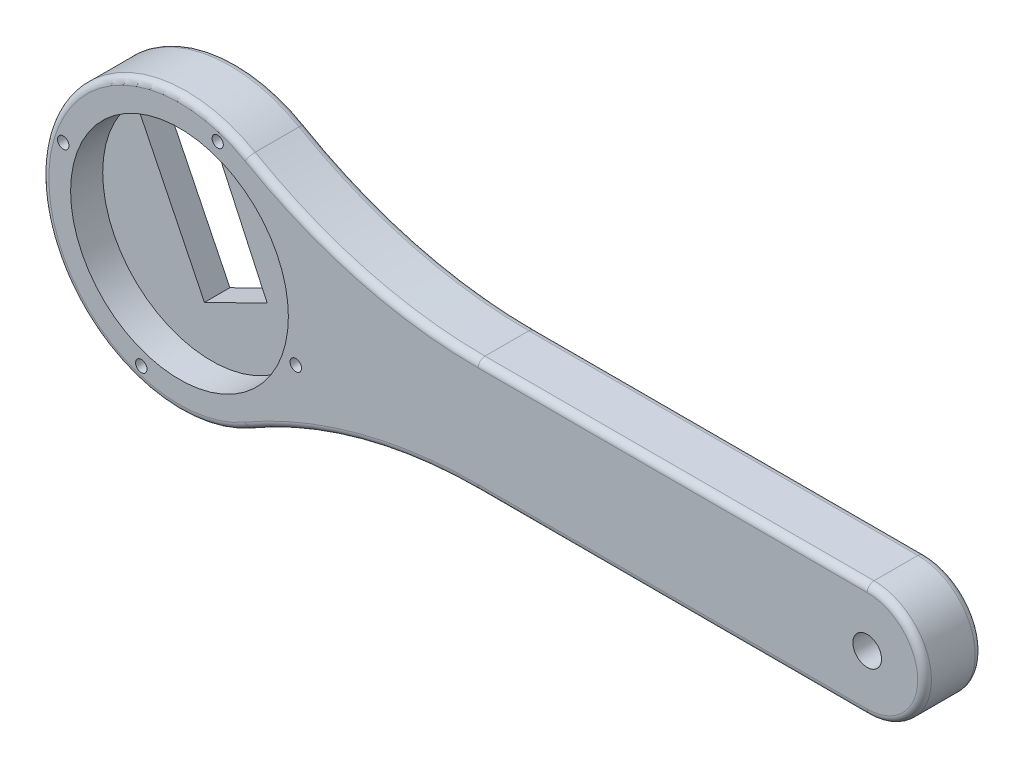
SolidWorks part; units mm, degrees
ref_plane "Front Plane" through (0, 0, 0) normal (0, 0, 1) x (1, 0, 0)
ref_plane "Top Plane" through (0, 0, 0) normal (0, 1, 0) x (1, 0, 0)
ref_plane "Right Plane" through (0, 0, 0) normal (1, 0, 0) x (0, 0, -1)
sketch "Sketch1" plane through (0, 0, 0) normal (0, 0, 1) x (1, 0, 0)
  line L0 (0, 0) -> (300, 0) construction
  line L1 (54.5436, 25) -> (300, 25)
  line L2 (54.5436, -25) -> (300, -25)
  arc A0 (54.5436, 25) -> (54.5436, -25) centre (0, 0) ccw
  arc A2 (300, -25) -> (300, 25) centre (300, 0) ccw
  circle A3 centre (300, 0) radius 6.25
  dimension "D1" = 120
  dimension "D2" = 50
  dimension "D5" = 12.5
  dimension "D3" = 300
  dimension "D4" = 245.4564
extrude "Boss-Extrude1" add sketch "Sketch1" along normal blind 25.1
sketch "Sketch2" plane through (0, 0, 25.1) normal (0, 0, 1) x (1, 0, 0)
  circle A0 centre (-16.6647, -50.7331) radius 2.495
  circle A1 centre (-50.7331, 16.6647) radius 2.5
  circle A2 centre (16.6647, 50.7331) radius 2.4444
  circle A3 centre (50.7331, -16.6647) radius 2.5
sketch "Sketch3" plane through (0, 0, 25.1) normal (0, 0, 1) x (1, 0, 0)
  circle A0 centre (0, 0) radius 47.5
  dimension "D1" = 95
extrude "Cut-Extrude2" cut sketch "Sketch3" against normal blind 14
extrude "Cut-Extrude5" cut sketch "Sketch2" against normal through all both and the other way through all
sketch "Sketch6" plane through (0, 0, 0) normal (0, 0, -1) x (-1, 0, 0)
  circle A0 centre (11.9735, 47.2126) radius 3
  circle A1 centre (27.3813, 40.0293) radius 3
  circle A2 centre (-19.7177, -20.7629) radius 3
  circle A3 centre (-4.3099, -27.9462) radius 3
  dimension "D1" = 6
  dimension "D2" = 6
  dimension "D3" = 6
  dimension "D4" = 6
extrude "Cut-Extrude6" cut sketch "Sketch6" against normal blind 6
sketch "Sketch7" plane through (0, 0, 11.1) normal (0, 0, 1) x (1, 0, 0)
  line L0 (-32.4009, 32.8719) -> (-3.109, -26.9124)
  line L1 (-3.109, -26.9124) -> (24.2542, -13.5055)
  line L2 (24.2542, -13.5055) -> (-3.6508, 46.9583)
  line L3 (-3.6508, 46.9583) -> (-32.4009, 32.8719)
  circle A0 centre (0, 0) radius 47.1 construction
extrude "Cut-Extrude7" cut sketch "Sketch7" against normal through all both and the other way through all
fillet "Fillet1" radius 200 2 edges at (54.5436, -25, 12.55) (54.5436, 25, 12.55)
fillet "Fillet2" radius 3 12 edges at (325, 0, 0) (215.1441, -25, 0) (78.4007, -31.848, 0) (-60, 0, 0) (78.4007, 31.848, 0) (325, 0, 25.1) (215.1441, -25, 25.1) (78.4007, -31.848, 25.1) (-60, 0, 25.1) (78.4007, 31.848, 25.1) (215.1441, 25, 0) (215.1441, 25, 25.1)
